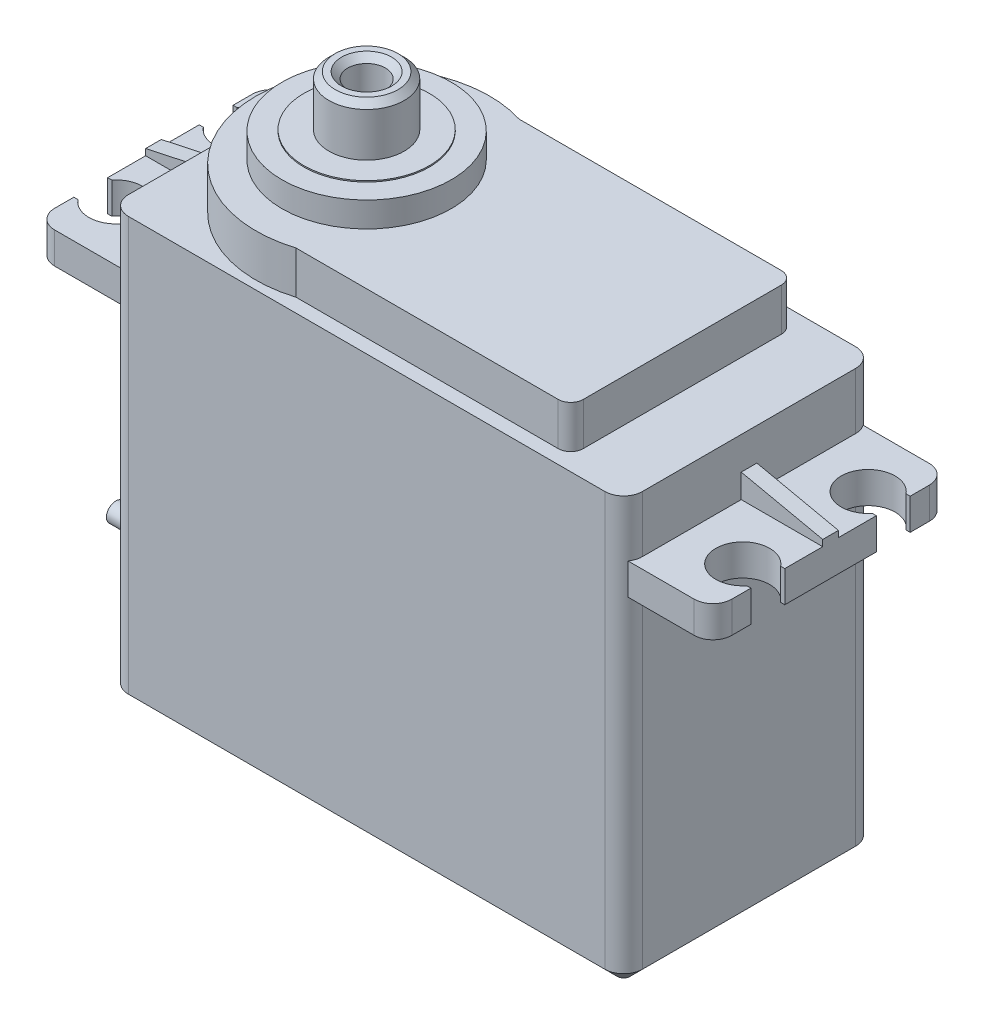
SolidWorks part; units mm, degrees
ref_plane "Front Plane" through (0, 0, 0) normal (0, 0, 1) x (1, 0, 0)
ref_plane "Top Plane" through (0, 0, 0) normal (0, 1, 0) x (1, 0, 0)
ref_plane "Right Plane" through (0, 0, 0) normal (1, 0, 0) x (0, 0, -1)
sketch "Sketch1" plane through (0, 0, 0) normal (0, 0, 1) x (1, 0, 0)
  line L0 (0, 17) -> (0, -17) construction
  line L1 (-20.5, 17) -> (20.5, 17)
  line L2 (-20.5, 17) -> (-20.5, -17)
  line L3 (-20.5, -17) -> (20.5, -17)
  line L4 (20.5, 17) -> (20.5, -17)
  dimension "D1" = 41
  dimension "D2" = 34
extrude "Extrude1" add sketch "Sketch1" along normal mid plane 20
sketch "Sketch2" plane through (0, 17, 0) normal (0, 1, 0) x (1, 0, 0)
  line L0 (-6.7337, -8.9) -> (14.18, -8.9)
  line L1 (15.18, -7.9) -> (15.18, 7.9)
  line L2 (14.18, 8.9) -> (-6.7337, 8.9)
  line L3 (20.5, -10) -> (20.5, 10) construction
  line L4 (20.5, -10) -> (-20.5, -10) construction
  arc A0 (-6.7337, 8.9) -> (-6.7337, -8.9) centre (-9.5, 0) ccw
  arc A1 (14.18, -8.9) -> (15.18, -7.9) centre (14.18, -7.9) ccw
  arc A2 (15.18, 7.9) -> (14.18, 8.9) centre (14.18, 7.9) ccw
  dimension "D1" = 9.32
  dimension "D5" = 1
  dimension "D2" = 17.8
  dimension "D3" = 17.8
  dimension "D4" = 15.8
  dimension "D6" = 1.4142
  dimension "D7" = 1
  dimension "D8" = 1.4142
  dimension "D9" = 20.9137
  dimension "D10" = 5.32
  dimension "D11" = 1.1
extrude "Extrude2" add sketch "Sketch2" along normal blind 3.4
sketch "Sketch3" plane through (0, 0, 0) normal (0, 0, 1) x (1, 0, 0)
  line L0 (-10, 20.4) -> (-16.75, 20.4)
  line L1 (-16.75, 20.4) -> (-16.75, 22.4)
  line L2 (-16.75, 22.4) -> (-15, 22.4)
  line L3 (-15, 22.4) -> (-15, 22.5)
  line L4 (-15, 22.5) -> (-10, 22.5)
  line L5 (-10, 22.5) -> (-10, 20.4)
  line L6 (-6.7337, 20.4) -> (-18.82, 20.4) construction
  dimension "D1" = 6.75
  dimension "D2" = 2
  dimension "D3" = 5
  dimension "D4" = 0.1
  dimension "D5" = 10
revolve "Revolve1" add sketch "Sketch3" angle 360 about L5
sketch "Sketch4" plane through (0, 22.5, 0) normal (0, 1, 0) x (1, 0, 0)
  circle A0 centre (-10, 0) radius 3
  circle A1 centre (-10, 0) radius 1.5
  dimension "D1" = 6
  dimension "D2" = 3
extrude "Extrude3" add sketch "Sketch4" along normal blind 4 separate body
fillet "Fillet1" radius 1.5 4 edges at (20.5, 0, -10) (20.5, 0, 10) (-20.5, 0, -10) (-20.5, 0, 10)
ref_plane "Plane1" through (0, 12.5, 0) normal (0, 1, 0) x (-1, 0, 0)
sketch "Sketch6" plane through (0, 12.5, 0) normal (0, 1, 0) x (-1, 0, 0)
  line L0 (0, 0) -> (0, -6.9138) construction
  line L1 (27, 0) -> (27, 3.65)
  line L2 (27, 3.65) -> (26.6733, 3.65)
  line L3 (26.6733, 6.35) -> (27, 6.35)
  line L4 (27, 6.35) -> (27, 7.875)
  line L5 (25.5, 9.375) -> (20.2183, 9.375)
  line L6 (20.5, 8.5) -> (20.5, 0)
  line L7 (20.5, 8.5) -> (20.5, -8.5) construction
  line L8 (20.5, 0) -> (27, 0) construction
  line L9 (20.5, -8.5) -> (20.5, 0)
  line L10 (25.5, -9.375) -> (20.2183, -9.375)
  line L11 (27, -6.35) -> (27, -7.875)
  line L12 (26.6733, -6.35) -> (27, -6.35)
  line L13 (27, -3.65) -> (26.6733, -3.65)
  line L14 (27, 0) -> (27, -3.65)
  arc A0 (26.6733, 6.35) -> (26.6733, 3.65) centre (25, 5) ccw
  arc A1 (27, 7.875) -> (25.5, 9.375) centre (25.5, 7.875) ccw
  arc A2 (20.5, 8.5) -> (20.2183, 9.375) centre (19, 8.5) ccw
  arc A3 (20.5, -8.5) -> (20.2183, -9.375) centre (19, -8.5) cw
  arc A4 (20.5, 8.5) -> (19, 10) centre (19, 8.5) ccw construction
  arc A5 (27, -7.875) -> (25.5, -9.375) centre (25.5, -7.875) cw
  arc A6 (26.6733, -6.35) -> (26.6733, -3.65) centre (25, -5) cw
  arc A7 (19, -10) -> (20.5, -8.5) centre (19, -8.5) ccw construction
  dimension "D1" = 2.15
  dimension "D5" = 1.5
  dimension "D8" = 1.5
  dimension "D2" = 54
  dimension "D3" = 50
  dimension "D6" = 0.875
  dimension "D7" = 0.2817
  dimension "D9" = 1.5
  dimension "D10" = 2.1213
  dimension "D11" = 2.7
  dimension "D12" = 1.525
extrude "Extrude4" add sketch "Sketch6" against normal blind 2.5
sketch "Sketch7" plane through (0, 0, 0) normal (0, 0, 1) x (1, 0, 0)
  line L0 (-20.5, 14.4) -> (-27, 13)
  line L1 (-27, 13) -> (-27, 12.5)
  line L2 (-27, 12.5) -> (-20.5, 12.5)
  line L3 (-20.5, 12.5) -> (-20.5, 14.4)
  line L5 (-27, 10) -> (-27, 12.5) construction
  line L6 (-20.5, 12.5) -> (-20.5, 17) construction
  line L7 (-25.5, 12.5) -> (-20.2183, 12.5) construction
  dimension "D1" = 0.5
  dimension "D2" = 1.9
extrude "Extrude5" add sketch "Sketch7" along normal mid plane 1.25
mirror "Mirror1" about plane through (0, 0, 0) normal (1, 0, 0) of "Extrude5", "Extrude4"
sketch "Sketch8" plane through (-20.5, 0, 0) normal (-1, 0, 0) x (0, 0, 1)
  line L0 (8.5, -17) -> (-8.5, -17) construction
  circle A0 centre (0, -12.4) radius 0.75
  point P2 (0, -17)
  dimension "D1" = 4.6
  dimension "D2" = 1.5
extrude "Extrude6" add sketch "Sketch8" along normal blind 8 separate body
sketch "Sketch9" plane through (-20.5, 0, 0) normal (-1, 0, 0) x (0, 0, 1)
  line L0 (8.5, -17) -> (-8.5, -17) construction
  circle A0 centre (1.5, -12.4) radius 0.75
  circle A1 centre (0, -12.4) radius 0.75 construction
  dimension "D1" = 4.6
extrude "Extrude7" add sketch "Sketch9" along normal blind 8 separate body
sketch "Sketch10" plane through (-20.5, 0, 0) normal (-1, 0, 0) x (0, 0, 1)
  line L0 (8.5, -17) -> (-8.5, -17) construction
  circle A0 centre (-1.5, -12.4) radius 0.75
  circle A1 centre (0, -12.4) radius 0.75 construction
  dimension "D1" = 4.6
extrude "Extrude8" add sketch "Sketch10" along normal blind 8 separate body
chamfer "Chamfer1" distance 1 angle 45 8 edges at (-20.0607, -17, -9.5607) (-20.5, -17, 0) (-20.0607, -17, 9.5607) (0, -17, 10) (20.0607, -17, 9.5607) (20.5, -17, 0) (20.0607, -17, -9.5607) (0, -17, -10)
chamfer "Chamfer2" distance 0.5 angle 45 2 edges at (-10, 26.5, 3) (-10, 26.5, 1.5)
sketch "Sketch11" plane through (-20.5, 0, 0) normal (-1, 0, 0) x (0, 0, 1)
  line L0 (0, 10) -> (0, -17) construction
  line L1 (8.5, 10) -> (-8.5, 10) construction
  line L2 (8.5, -17) -> (-8.5, -17) construction
  line L3 (-3.65, 10) -> (3.65, 10) construction
  circle A0 centre (0, 0) radius 1.5
  dimension "D1" = 3
  dimension "D2" = 10
extrude "Cut-Extrude1" cut sketch "Sketch11" against normal blind 5
